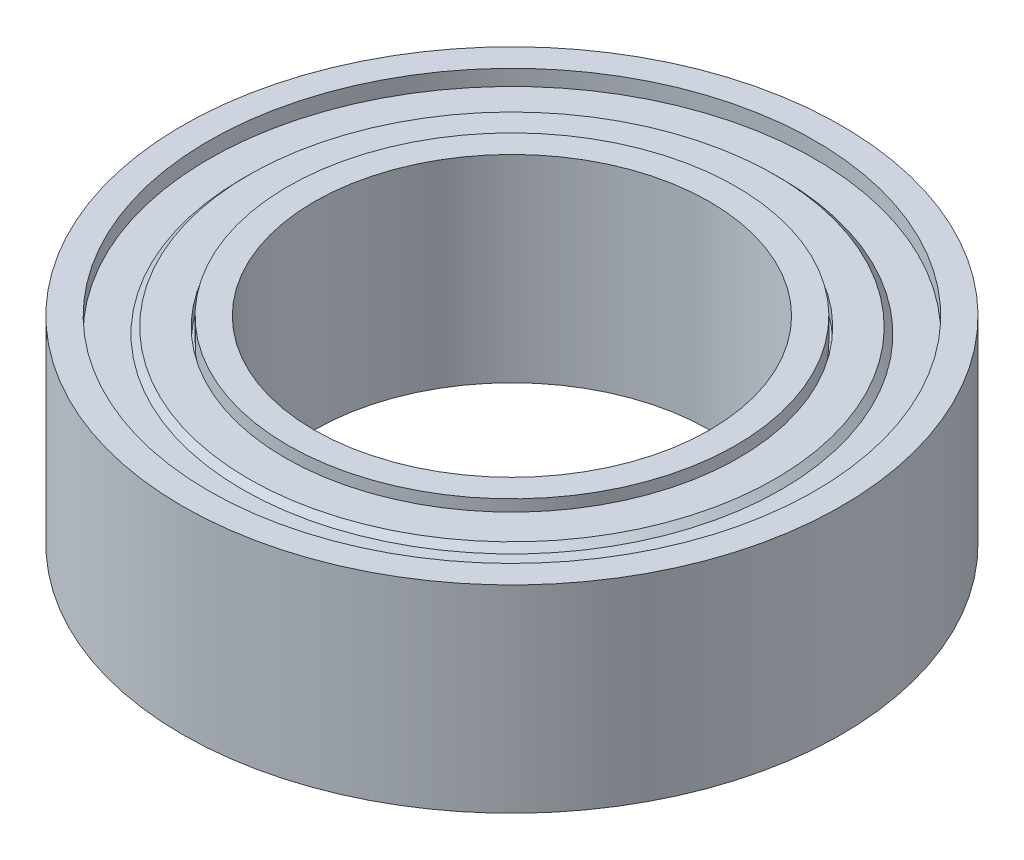
SolidWorks part; units mm, degrees
ref_plane "Front Plane" through (0, 0, 0) normal (0, 0, 1) x (1, 0, 0)
ref_plane "Top Plane" through (0, 0, 0) normal (0, 1, 0) x (1, 0, 0)
ref_plane "Right Plane" through (0, 0, 0) normal (1, 0, 0) x (0, 0, -1)
sketch "Sketch1" plane through (0, 0, 0) normal (1, 0, 0) x (0, 0, -1)
  line L0 (-5, 0) -> (-5, -1.5)
  line L1 (0, 0) -> (-64.4653, 0) construction
  line L2 (-5, -1.5) -> (-4.6, -1.5)
  line L3 (-4.6, -1.5) -> (-4.6, -1.2614)
  line L4 (0, 0) -> (0, -106.3845) construction
  line L5 (-4.6, -1.2614) -> (-4.0869, -1.2614)
  line L6 (-4.0869, -1.2614) -> (-3.9936, -1.3547)
  line L7 (-3.9936, -1.3547) -> (-3.4414, -1.3547)
  line L8 (-3.4414, -1.3547) -> (-3.4414, -1.1388)
  line L9 (-3.4414, -1.1388) -> (-3.4, -1.1388)
  line L10 (-3.4, -1.1388) -> (-3.4, -1.5)
  line L11 (-3.4, -1.5) -> (-3, -1.5)
  line L12 (-3, -1.5) -> (-3, 0)
  line L13 (-3, 0) -> (-5, 0)
  dimension "D1" = 5
  dimension "D2" = 3
  dimension "D3" = 0.4
  dimension "D4" = 0.4
  dimension "D5" = 1.5
revolve "Revolve1" add sketch "Sketch1" angle 360 about L4
mirror "Mirror1" about plane through (0, 0, 3) normal (0, 1, 0) of "Revolve1"
